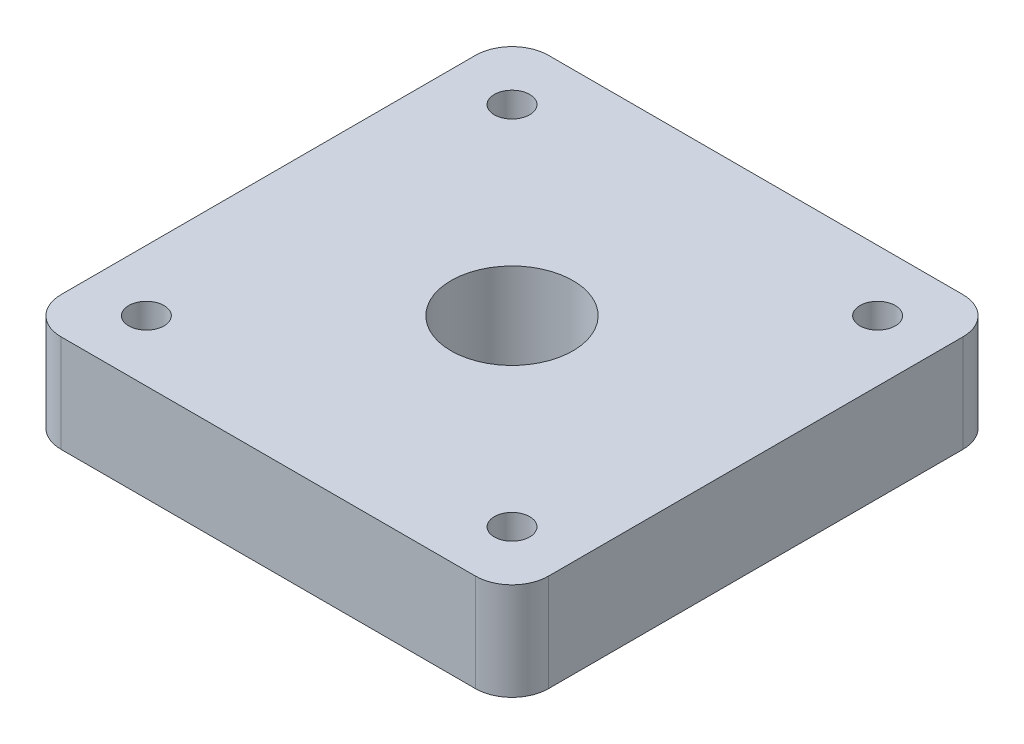
SolidWorks part; units mm, degrees
material "Oak"
ref_plane "Front Plane" through (0, 0, 0) normal (0, 0, 1) x (1, 0, 0)
ref_plane "Top Plane" through (0, 0, 0) normal (0, 1, 0) x (1, 0, 0)
ref_plane "Right Plane" through (0, 0, 0) normal (1, 0, 0) x (0, 0, -1)
sketch "Sketch1" plane through (0, 0, 0) normal (0, 1, 0) x (1, 0, 0)
  line L1 (0, 0.1114) -> (40, 0.1114)
  line L2 (0, 0.1114) -> (0, -39.8886)
  line L3 (0, -39.8886) -> (40, -39.8886)
  line L4 (40, 0.1114) -> (40, -39.8886)
  circle A0 centre (20, -19.8886) radius 5
  dimension "D5" = 10
  dimension "D1" = 40
  dimension "D2" = 40
  dimension "D3" = 20
  dimension "D4" = 20
extrude "Boss-Extrude1" add sketch "Sketch1" along normal blind 8
sketch "Sketch12" plane through (0, 8, 0) normal (0, 1, 0) x (1, 0, 0)
  line L0 (40, 0.1114) -> (0, 0.1114) construction
  line L1 (0, 0.1114) -> (0, -39.8886) construction
  line L2 (40, -39.8886) -> (40, 0.1114) construction
  line L3 (0, -39.8886) -> (40, -39.8886) construction
  circle A0 centre (5, -4.8886) radius 1.45
  circle A1 centre (35, -4.8886) radius 1.45
  circle A2 centre (35, -34.8886) radius 1.45
  circle A3 centre (5, -34.8886) radius 1.45
  dimension "D1" = 2.9
  dimension "D2" = 2.9
  dimension "D3" = 2.9
  dimension "D4" = 2.9
  dimension "D5" = 5
  dimension "D6" = 5
  dimension "D7" = 5
  dimension "D8" = 5
  dimension "D9" = 5
  dimension "D10" = 5
  dimension "D11" = 5
  dimension "D12" = 5
extrude "Cut-Extrude1" cut sketch "Sketch12" against normal through all
fillet "Fillet1" radius 3 4 edges at (40, 4, 39.8886) (40, 4, -0.1114) (0, 4, -0.1114) (0, 4, 39.8886)
